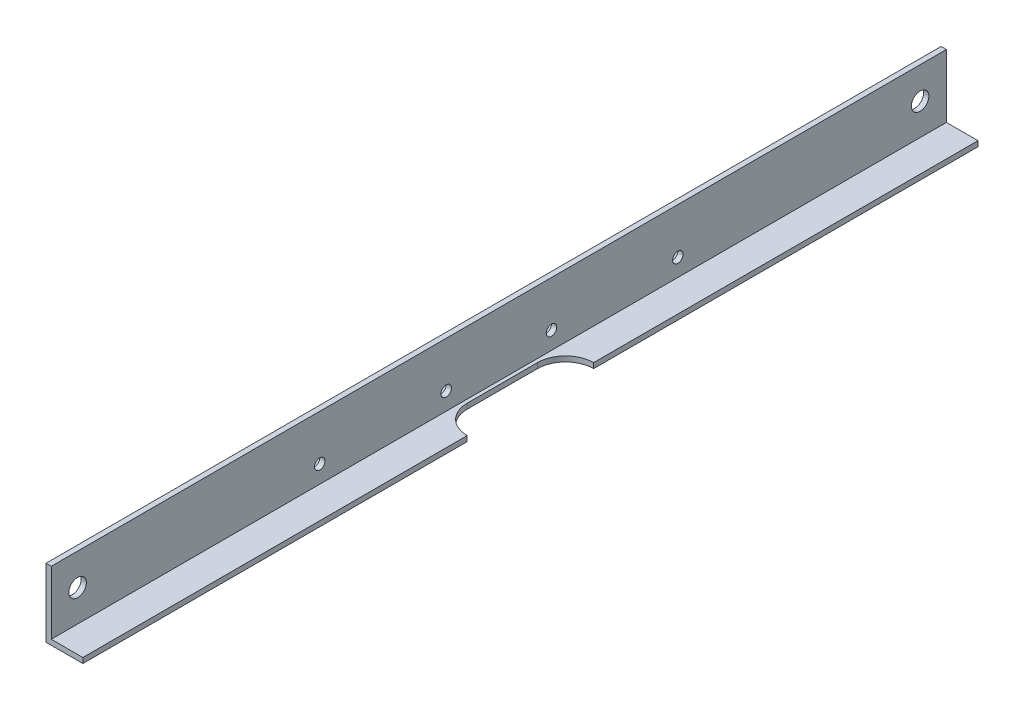
SolidWorks part; units mm, degrees
material "3.0205 (EN-AW 1200)"
ref_plane "Plan de face" through (0, 0, 0) normal (0, 0, 1) x (1, 0, 0)
ref_plane "Plan de dessus" through (0, 0, 0) normal (0, 1, 0) x (1, 0, 0)
ref_plane "Plan de droite" through (0, 0, 0) normal (1, 0, 0) x (0, 0, -1)
sketch "Esquisse1" plane through (0, 0, 0) normal (0, 0, 1) x (1, 0, 0)
  line L1 (-9.75, 0) -> (9.75, 0)
  dimension "D2" = 19.5
extrude "Extru.-Mince1" add sketch "Esquisse1" along normal mid plane 255 thin thin type one direction reverse wall 1.5
sketch "Esquisse2" plane through (0, 0, -127.5) normal (0, 0, -1) x (-1, 0, 0)
  line L0 (0, 0) -> (0, 19.5)
  dimension "D1" = 19.5
extrude "Extru.-Mince2" add sketch "Esquisse2" against normal up to surface (255 mm away) thin up to face at (0, 0.75, 127.5) thin type mid plane wall 1.5
sketch "Esquisse3" plane through (0, 1.5, 0) normal (0, 1, 0) x (1, 0, 0)
  line L0 (-8.75, 127.5) -> (-8.75, 110) construction
  line L1 (-9.75, 127.5) -> (-0.75, 127.5) construction
  line L2 (-0.75, 127.5) -> (-0.75, 110)
  line L3 (-16.75, 127.5) -> (-16.75, 110)
  line L4 (9.75, 10) -> (9.75, -10) construction
  line L5 (17.75, 10) -> (17.75, -10)
  line L6 (1.75, 10) -> (1.75, -10)
  line L8 (-8.75, -127.5) -> (-8.75, -110) construction
  line L9 (-9.75, -127.5) -> (-0.75, -127.5) construction
  line L10 (-16.75, -127.5) -> (-16.75, -110)
  line L11 (-0.75, -127.5) -> (-0.75, -110)
  line L12 (-0.75, -127.5) -> (-0.75, 127.5) construction
  line L13 (9.75, -127.5) -> (9.75, 127.5) construction
  arc A0 (-0.75, 127.5) -> (-16.75, 127.5) centre (-8.75, 127.5) ccw
  arc A1 (-16.75, 110) -> (-0.75, 110) centre (-8.75, 110) ccw
  arc A2 (17.75, 10) -> (1.75, 10) centre (9.75, 10) ccw
  arc A3 (1.75, -10) -> (17.75, -10) centre (9.75, -10) ccw
  arc A4 (-16.75, -127.5) -> (-0.75, -127.5) centre (-8.75, -127.5) ccw
  arc A5 (-0.75, -110) -> (-16.75, -110) centre (-8.75, -110) ccw
  point P4 (-8.75, 118.75)
  point P9 (9.75, 0)
  point P23 (-8.75, -118.75)
  dimension "D3" = 20
  dimension "D1" = 16
  dimension "D2" = 220
extrude "Enlèv. mat.-Extru.1" cut sketch "Esquisse3" against normal through all
sketch "Esquisse4" plane through (0.75, 0, 0) normal (1, 0, 0) x (0, 0, -1)
  line L0 (0, 0) -> (0, 19.5) construction
  line L1 (-127.5, 19.5) -> (127.5, 19.5) construction
  circle A0 centre (-120, 10.5) radius 2.5
  circle A1 centre (120, 10.5) radius 2.5
  dimension "D1" = 240
  dimension "D2" = 5
  dimension "D3" = 9
extrude "Enlèv. mat.-Extru.2" cut sketch "Esquisse4" against normal through all
sketch "Esquisse5" plane through (0, 0, 0) normal (0, -1, 0) x (1, 0, 0)
  line L0 (0, 0) -> (-9.75, 0) construction
  line L1 (-9.75, 102.0627) -> (-9.75, -102.0627) construction
  line L2 (-0.75, 127.5) -> (9.75, 127.5) construction
  circle A0 centre (-5.75, 59) radius 1.5
  circle A1 centre (-5.75, -59) radius 1.5
  dimension "D1" = 118
  dimension "D2" = 68.5
  dimension "D3" = 3
  dimension "D4" = 4
extrude "Enlèv. mat.-Extru.3" cut sketch "Esquisse5" against normal through all
sketch "Esquisse6" plane through (0.75, 0, 0) normal (1, 0, 0) x (0, 0, -1)
  line L0 (0, 0) -> (0, 19.5) construction
  line L1 (-127.5, 19.5) -> (127.5, 19.5) construction
  line L2 (127.5, 1.5) -> (-127.5, 1.5) construction
  circle A0 centre (-51, 6.5) radius 1.5
  circle A1 centre (-15, 6.5) radius 1.5
  circle A2 centre (15, 6.5) radius 1.5
  circle A3 centre (51, 6.5) radius 1.5
  dimension "D1" = 3
  dimension "D2" = 30
  dimension "D3" = 102
  dimension "D4" = 5
  dimension "D5" = 5
extrude "Enlèv. mat.-Extru.4" cut sketch "Esquisse6" against normal through all
